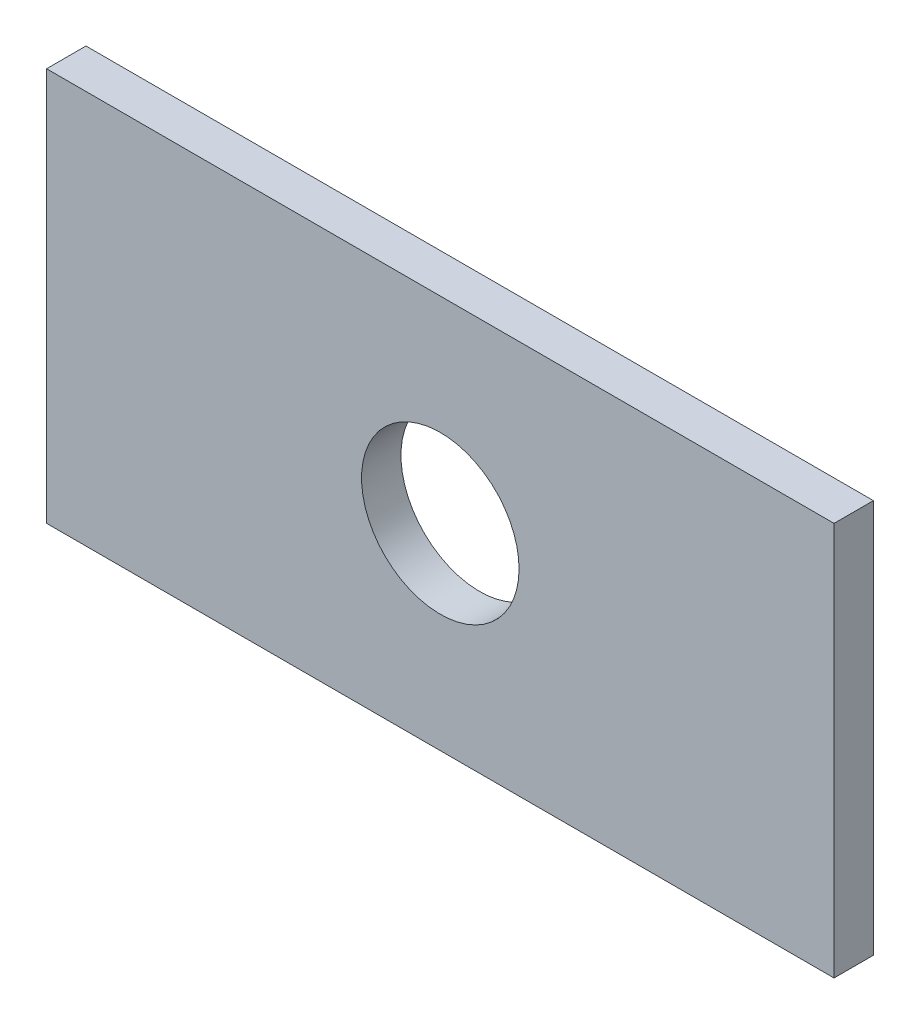
SolidWorks part; units mm, degrees
ref_plane "Спереди" through (0, 0, 0) normal (0, 0, 1) x (1, 0, 0)
ref_plane "Сверху" through (0, 0, 0) normal (0, 1, 0) x (1, 0, 0)
ref_plane "Справа" through (0, 0, 0) normal (1, 0, 0) x (0, 0, -1)
sketch "Эскиз2" plane through (0, 0, 0) normal (0, 0, 1) x (1, 0, 0)
  line L1 (100, -50) -> (-100, -50)
  line L2 (100, -50) -> (100, 50)
  line L3 (100, 50) -> (-100, 50)
  line L4 (-100, -50) -> (-100, 50)
  line L5 (100, -50) -> (-100, 50) construction
  line L6 (100, 50) -> (-100, -50) construction
  circle A0 centre (0, 0) radius 20
  point P0 (0, 0)
  dimension "D3" = 40
  dimension "D1" = 200
  dimension "D2" = 100
extrude "Бобышка-Вытянуть1" add sketch "Эскиз2" along normal blind 10
